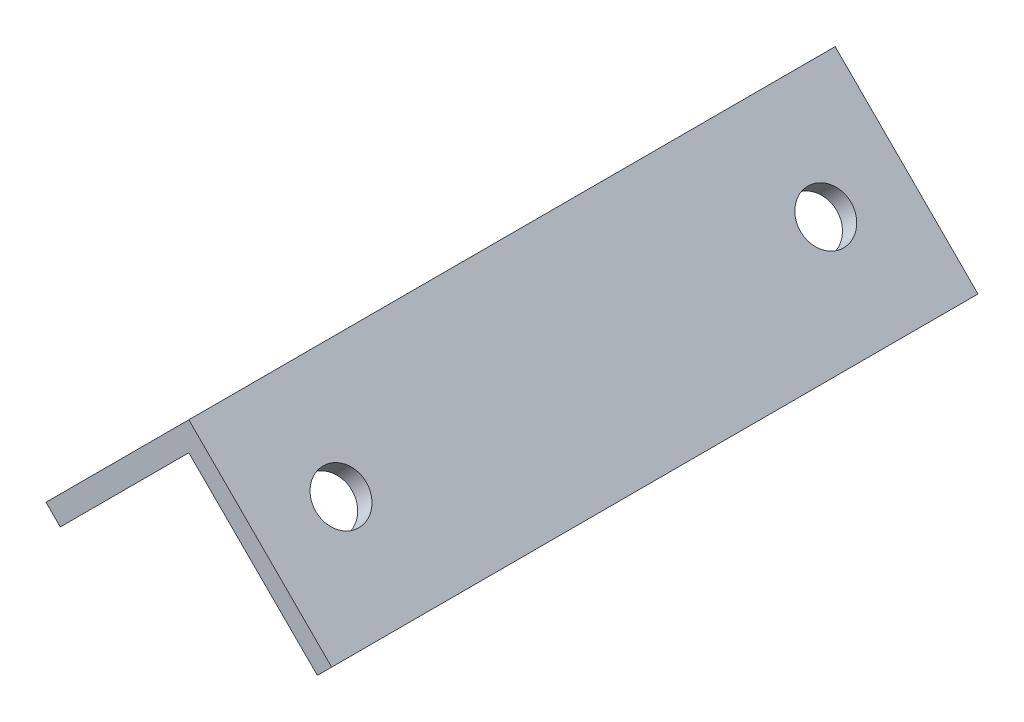
SolidWorks part; units mm, degrees
material "1060 Alloy"
ref_plane "Front Plane" through (0, 0, 0) normal (0, 0, 1) x (1, 0, 0)
ref_plane "Top Plane" through (0, 0, 0) normal (0, 1, 0) x (1, 0, 0)
ref_plane "Right Plane" through (0, 0, 0) normal (1, 0, 0) x (0, 0, -1)
sketch "Sketch1" plane through (0, 0, 0) normal (0, 0, 1) x (1, 0, 0)
  line L0 (0, 0) -> (22.4506, 22.4506)
  line L1 (22.4506, 22.4506) -> (44.9013, 0)
  line L2 (44.9013, 0) -> (42.6562, -2.2451)
  line L3 (42.6562, -2.2451) -> (22.4506, 17.9605)
  line L4 (22.4506, 17.9605) -> (2.2451, -2.2451)
  line L5 (2.2451, -2.2451) -> (0, 0)
  dimension "D1" = 31.75
  dimension "D2" = 3.175
extrude "Boss-Extrude1" add sketch "Sketch1" along normal blind 101.6
sketch "Sketch4" plane through (0, 0, 0) normal (-0.7071, 0.7071, 0) x (0, 0, 1)
  line L0 (31.75, 15.875) -> (50.8, 15.875) construction
  line L1 (50.8, 15.875) -> (69.85, 15.875) construction
  line L2 (50.8, 31.75) -> (50.8, 15.875) construction
  line L3 (101.6, 31.75) -> (0, 31.75) construction
  line L4 (50.8, 15.875) -> (50.8, 0) construction
  line L5 (101.6, 0) -> (0, 0) construction
  line L6 (0, 31.75) -> (0, 0) construction
  circle A0 centre (31.75, 15.875) radius 3.9751
  circle A1 centre (69.85, 15.875) radius 3.9751
  point P6 (50.8, 0)
  dimension "D1" = 7.9502
  dimension "D2" = 31.75
extrude "Cut-Extrude3" cut sketch "Sketch4" against normal through all
ref_plane "Plan1" through (0, -2.2451, 0) normal (0, 1, 0) x (-1, 0, 0)
sketch "Esquisse1" plane through (22.4506, 22.4506, 0) normal (0.7071, 0.7071, 0) x (-0.7071, 0.7071, 0)
  line L1 (-31.75, 101.6) -> (-31.75, 0) construction
  line L2 (0, 12.7) -> (-31.75, 12.7) construction
  line L3 (0, 101.6) -> (0, 0) construction
  line L5 (-31.75, 0) -> (0, 0) construction
  circle A0 centre (-15.875, 12.7) radius 3.9751
  point P8 (-15.875, 12.7)
  dimension "D1" = 12.7
  dimension "D3" = 7.9502
  dimension "D2" = 15.875
extrude "Enlèv. mat.-Extru.1" cut sketch "Esquisse1" against normal through all
ref_plane "Plan2" through (0, 0, 50.8) normal (0, 0, 1) x (1, 0, 0)
mirror "Symétrie1" about plane through (0, 0, 50.8) normal (0, 0, 1) of "Enlèv. mat.-Extru.1"
